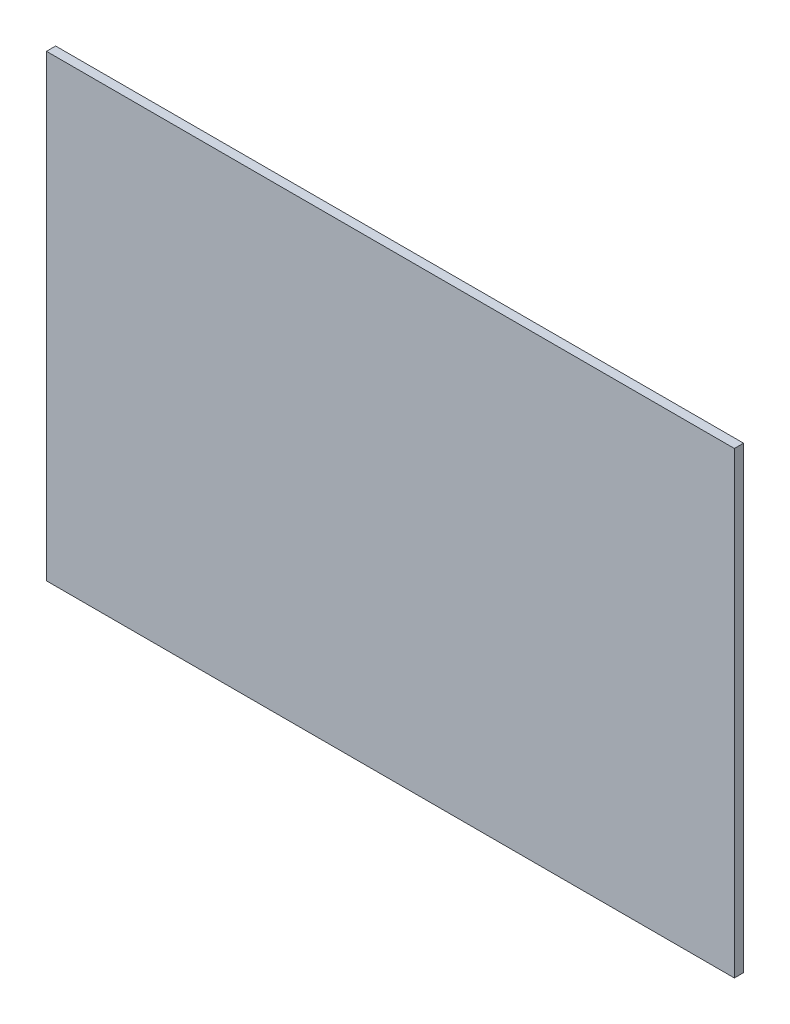
SolidWorks part; units mm, degrees
ref_plane "Front Plane" through (0, 0, 0) normal (0, 0, 1) x (1, 0, 0)
ref_plane "Top Plane" through (0, 0, 0) normal (0, 1, 0) x (1, 0, 0)
ref_plane "Right Plane" through (0, 0, 0) normal (1, 0, 0) x (0, 0, -1)
sketch "Sketch1" plane through (0, 0, 0) normal (0, 0, 1) x (1, 0, 0)
  line L1 (-150, 100) -> (150, 100)
  line L2 (-150, 100) -> (-150, -100)
  line L3 (-150, -100) -> (150, -100)
  line L4 (150, 100) -> (150, -100)
  dimension "D1" = 300
  dimension "D2" = 200
extrude "Boss-Extrude1" add sketch "Sketch1" along normal blind 4
